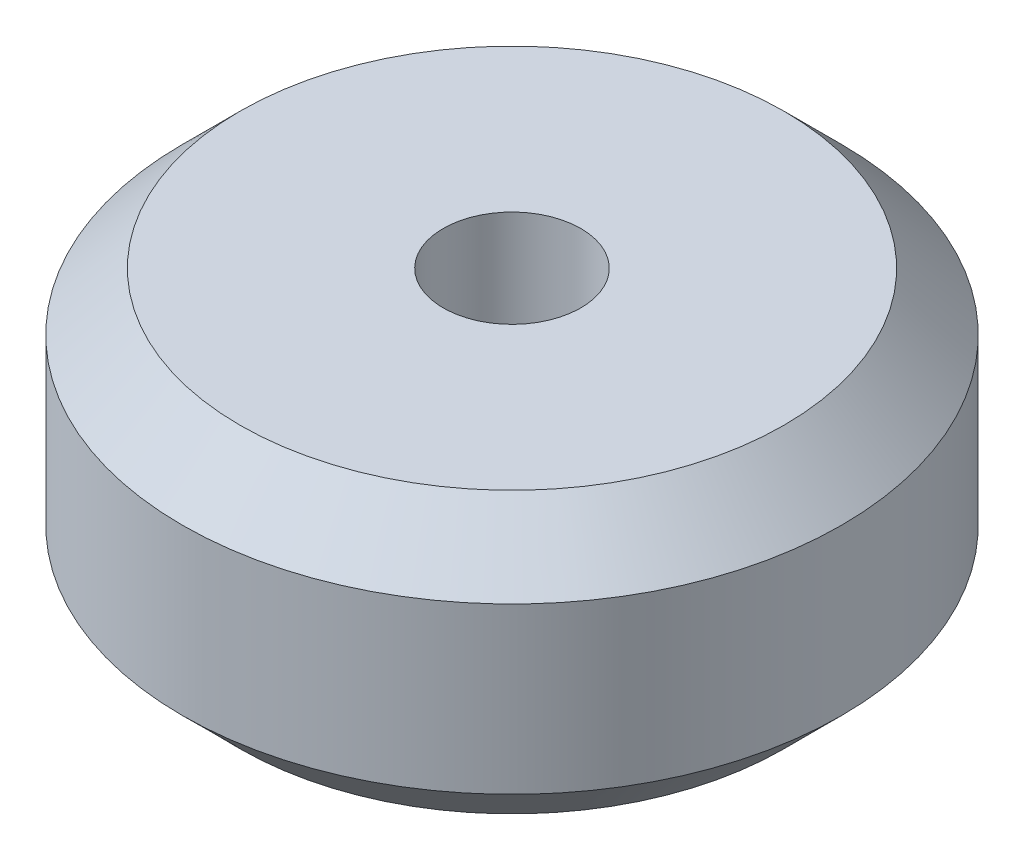
SolidWorks part; units mm, degrees
ref_plane "Front Plane" through (0, 0, 0) normal (0, 0, 1) x (1, 0, 0)
ref_plane "Top Plane" through (0, 0, 0) normal (0, 1, 0) x (1, 0, 0)
ref_plane "Right Plane" through (0, 0, 0) normal (1, 0, 0) x (0, 0, -1)
sketch "Sketch2" plane through (0, 0, 0) normal (0, 0, 1) x (1, 0, 0)
  line L0 (2.505, -5.1) -> (2.505, 5.1)
  line L1 (2.505, 5.1) -> (9.9, 5.1)
  line L2 (9.9, 5.1) -> (12, 3)
  line L3 (12, 3) -> (12, -3)
  line L4 (12, -3) -> (9.9, -5.1)
  line L5 (9.9, -5.1) -> (2.505, -5.1)
  line L6 (0, 0) -> (0, 5.4797) construction
  line L7 (0, 0) -> (12, 0) construction
  point P9 (2.505, 0)
  dimension "D1" = 5.01
  dimension "D2" = 24
  dimension "D3" = 6
  dimension "D4" = 10.2
revolve "Revolve1" add sketch "Sketch2" angle 360 about L6
